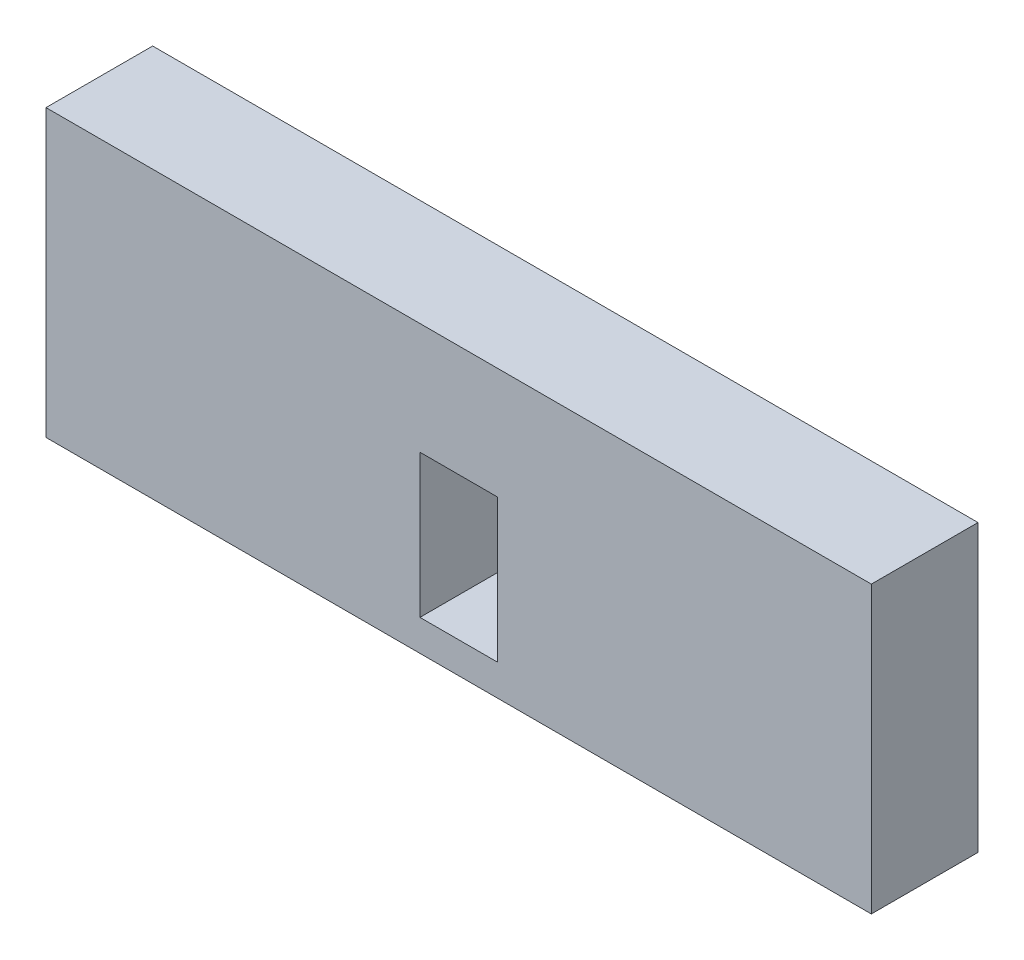
SolidWorks part; units mm, degrees
material "Papel canelado"
ref_plane "Plano frontal" through (0, 0, 0) normal (0, 0, 1) x (1, 0, 0)
ref_plane "Plano superior" through (0, 0, 0) normal (0, 1, 0) x (1, 0, 0)
ref_plane "Plano direito" through (0, 0, 0) normal (1, 0, 0) x (0, 0, -1)
sketch "Esboço1" plane through (0, 0, 0) normal (0, 0, 1) x (1, 0, 0)
  line L1 (0, 0) -> (130, 0)
  line L2 (0, 0) -> (0, 45)
  line L3 (0, 45) -> (130, 45)
  line L4 (130, 0) -> (130, 45)
  dimension "D1" = 45
  dimension "D2" = 130
extrude "Ressalto-extrusão1" add sketch "Esboço1" along normal blind 16.8
sketch "Esboço2" plane through (0, 0, 16.8) normal (0, 0, 1) x (1, 0, 0)
  line L0 (65, -955) -> (65, 49045) construction
  line L1 (58.9, 4.91) -> (71.1, 4.91)
  line L2 (58.9, 4.91) -> (58.9, 27.44)
  line L3 (58.9, 27.44) -> (71.1, 27.44)
  line L4 (71.1, 4.91) -> (71.1, 27.44)
  line L5 (130, 45) -> (0, 45) construction
  line L6 (0, 0) -> (130, 0) construction
  point P4 (65, 27.44)
  point P10 (65, 45)
  dimension "D1" = 12.2
  dimension "D2" = 22.53
  dimension "D3" = 4.91
extrude "Corte-extrusão1" cut sketch "Esboço2" against normal through all
